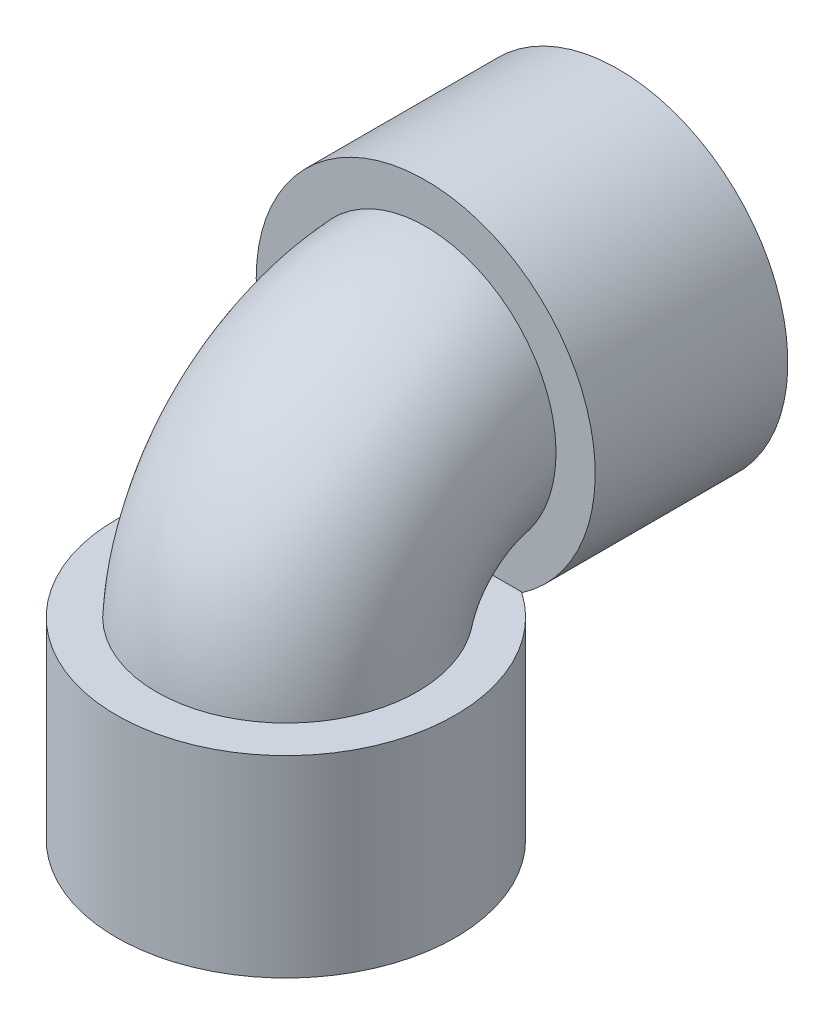
SolidWorks part; units mm, degrees
material "PVC Rígido"
ref_plane "Plan de face" through (0, 0, 0) normal (0, 0, 1) x (1, 0, 0)
ref_plane "Plan de dessus" through (0, 0, 0) normal (0, 1, 0) x (1, 0, 0)
ref_plane "Plan de droite" through (0, 0, 0) normal (1, 0, 0) x (0, 0, -1)
sketch "Esquisse1" plane through (0, 0, 0) normal (0, 0, 1) x (1, 0, 0)
  line L0 (0, -20.7453) -> (41.9598, -20.7453)
  circle A0 centre (0, 0) radius 16.9
revolve "Révol.-Mince1" add sketch "Esquisse1" angle 90 about L0
sketch "Esquisse2" plane through (0, 0, 0) normal (0, 0, -1) x (-1, 0, 0)
  circle A0 centre (0, 0) radius 13.9
extrude "Extru.-Mince1" add sketch "Esquisse2" along normal blind 22.4 thin
sketch "Esquisse3" plane through (0, -20.7453, 0) normal (0, -1, 0) x (1, 0, 0)
  circle A0 centre (0, 20.7453) radius 16.1
extrude "Extru.-Mince2" add sketch "Esquisse3" along normal blind 22.3 thin
sketch "Croquis1" plane through (0, -43.0453, 0) normal (0, -1, 0) x (1, 0, 0)
  circle A0 centre (0, 20.7453) radius 13.9 construction
  circle A1 centre (0, 20.7453) radius 13.9
  circle A2 centre (0, 20.7453) radius 22
  dimension "D1" = 44
extrude "Saliente-Extruir1" add sketch "Croquis1" against normal blind 25
sketch "Croquis2" plane through (0, 0, -22.4) normal (0, 0, -1) x (-1, 0, 0)
  circle A0 centre (0, 0) radius 13.9 construction
  circle A1 centre (0, 0) radius 13.9
  circle A2 centre (0, 0) radius 22
  dimension "D1" = 44
extrude "Saliente-Extruir2" add sketch "Croquis2" against normal blind 25
